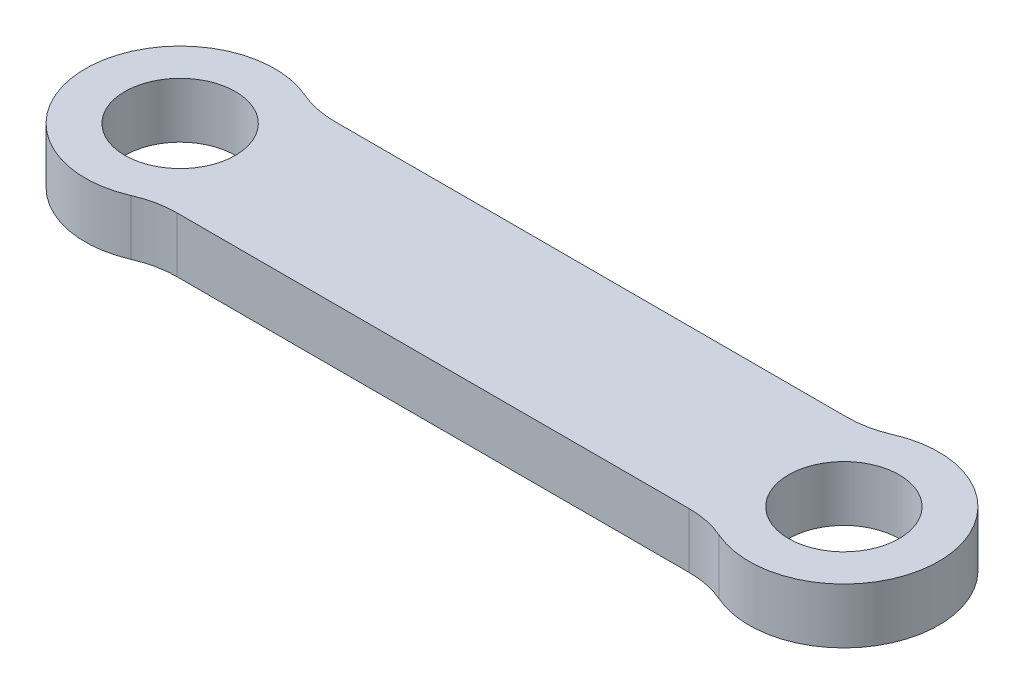
SolidWorks part; units mm, degrees
ref_plane "Front Plane" through (0, 0, 0) normal (0, 0, 1) x (1, 0, 0)
ref_plane "Top Plane" through (0, 0, 0) normal (0, 1, 0) x (1, 0, 0)
ref_plane "Right Plane" through (0, 0, 0) normal (1, 0, 0) x (0, 0, -1)
sketch "Sketch1" plane through (0, 0, 0) normal (0, 1, 0) x (1, 0, 0)
  line L0 (0, 0) -> (21, 0) construction
  line L1 (1.6583, 2.5) -> (19.3417, 2.5)
  line L2 (1.6583, -2.5) -> (19.3417, -2.5)
  circle A0 centre (0, 0) radius 3
  circle A1 centre (21, 0) radius 3
  circle A2 centre (0, 0) radius 1.75
  circle A3 centre (21, 0) radius 1.75
  dimension "D1" = 6
  dimension "D3" = 6
  dimension "D5" = 3.5
  dimension "D6" = 3.5
  dimension "D2" = 21
  dimension "D4" = 2.5
extrude "Boss-Extrude1" add sketch "Sketch1" along normal blind 1.75
fillet "Fillet1" radius 3 4 edges at (1.6583, 0.875, 2.5) (19.3417, 0.875, 2.5) (19.3417, 0.875, -2.5) (1.6583, 0.875, -2.5)
